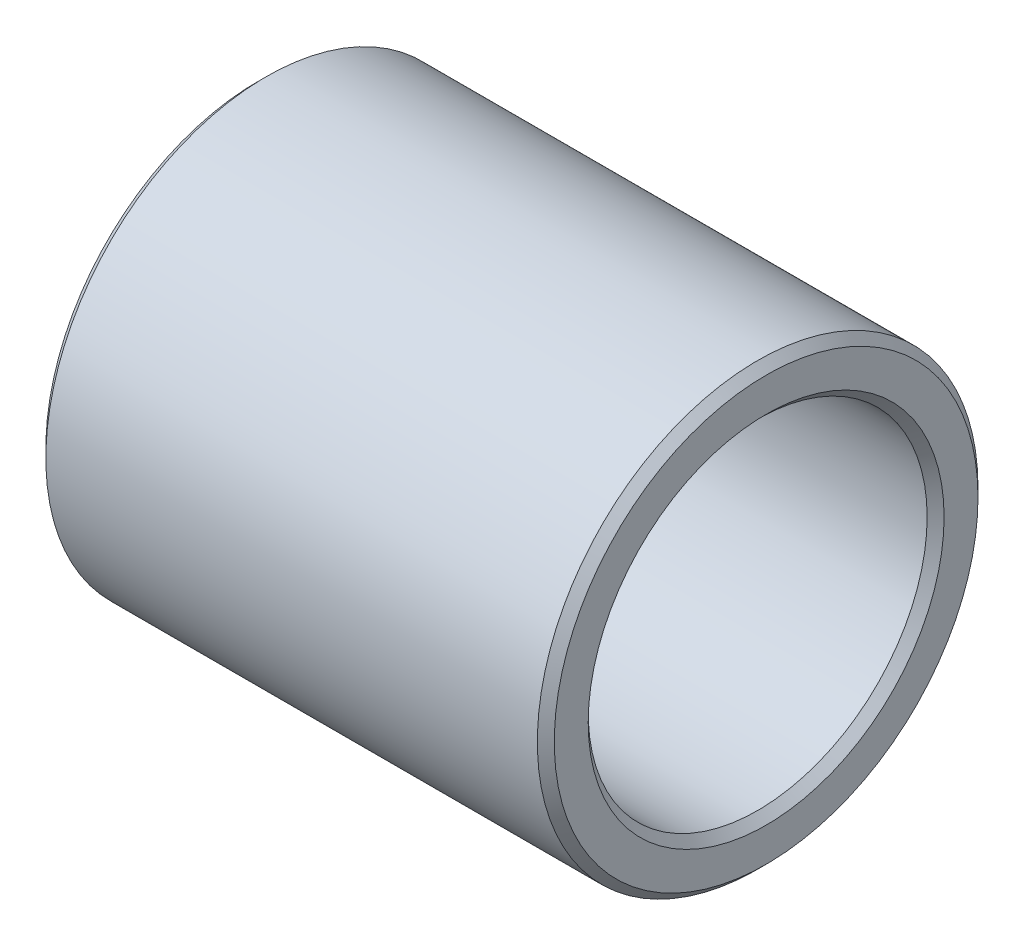
SolidWorks part; units mm, degrees
ref_plane "Front Plane" through (0, 0, 0) normal (0, 0, 1) x (1, 0, 0)
ref_plane "Top Plane" through (0, 0, 0) normal (0, 1, 0) x (1, 0, 0)
ref_plane "Right Plane" through (0, 0, 0) normal (1, 0, 0) x (0, 0, -1)
sketch "Sketch1" plane through (0, 0, 0) normal (1, 0, 0) x (0, 0, -1)
  circle A0 centre (0, 0) radius 13
  circle A1 centre (0, 0) radius 10
  dimension "D1" = 20
  dimension "D2" = 26
extrude "Boss-Extrude1" add sketch "Sketch1" along normal blind 30
fillet "Fillet1" radius 0.5 4 edges at (0, 0, -13) (30, 0, -13) (0, 0, -10) (30, 0, -10) profile chamfer
